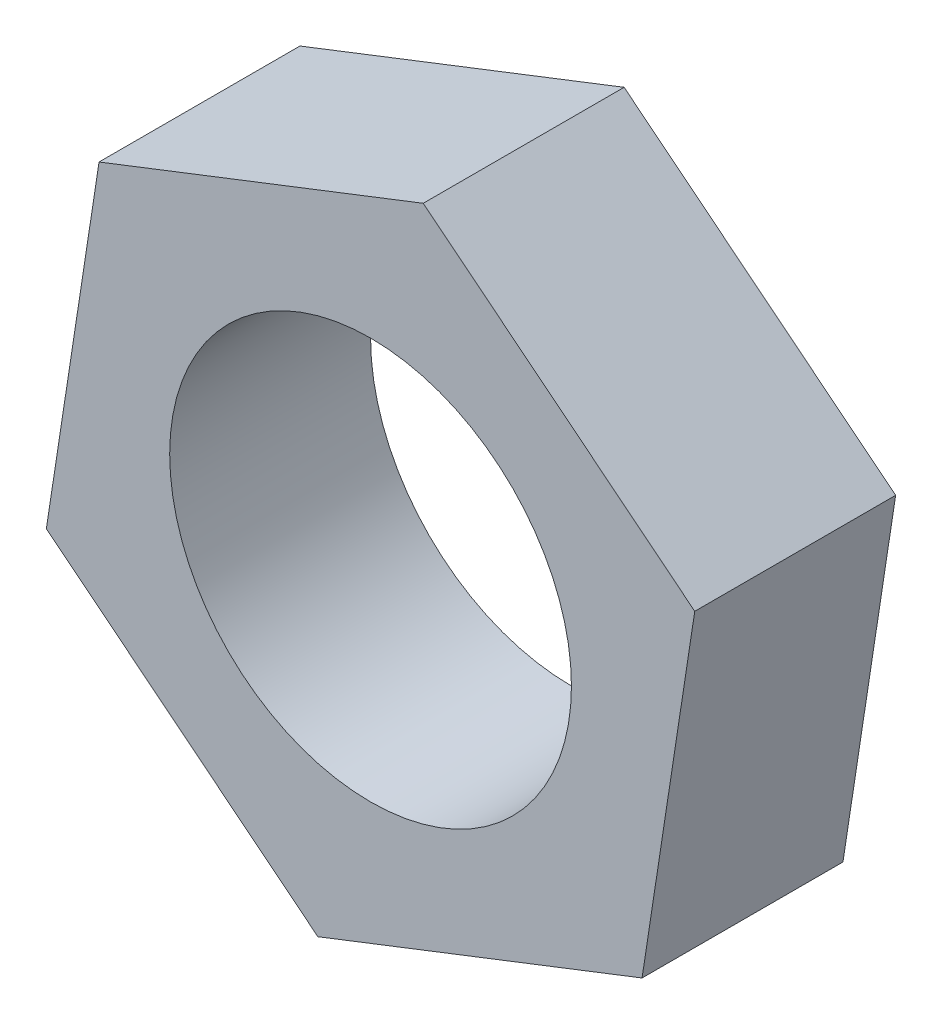
SolidWorks part; units mm, degrees
ref_plane "Front Plane" through (0, 0, 0) normal (0, 0, 1) x (1, 0, 0)
ref_plane "Top Plane" through (0, 0, 0) normal (0, 1, 0) x (1, 0, 0)
ref_plane "Right Plane" through (0, 0, 0) normal (1, 0, 0) x (0, 0, -1)
sketch "Sketch2" plane through (0, 0, 0) normal (0, 0, 1) x (1, 0, 0)
  line L1 (1.3516, -1.0832) -> (1.6138, 0.6289)
  line L2 (1.6138, 0.6289) -> (0.2623, 1.7121)
  line L3 (0.2623, 1.7121) -> (-1.3516, 1.0832)
  line L4 (-1.3516, 1.0832) -> (-1.6138, -0.6289)
  line L5 (-1.6138, -0.6289) -> (-0.2623, -1.7121)
  line L6 (-0.2623, -1.7121) -> (1.3516, -1.0832)
  circle A0 centre (0, 0) radius 1
  circle A1 centre (0, 0) radius 1.5 construction
  dimension "D1" = 2
  dimension "D2" = 3
extrude "Boss-Extrude1" add sketch "Sketch2" along normal blind 1
